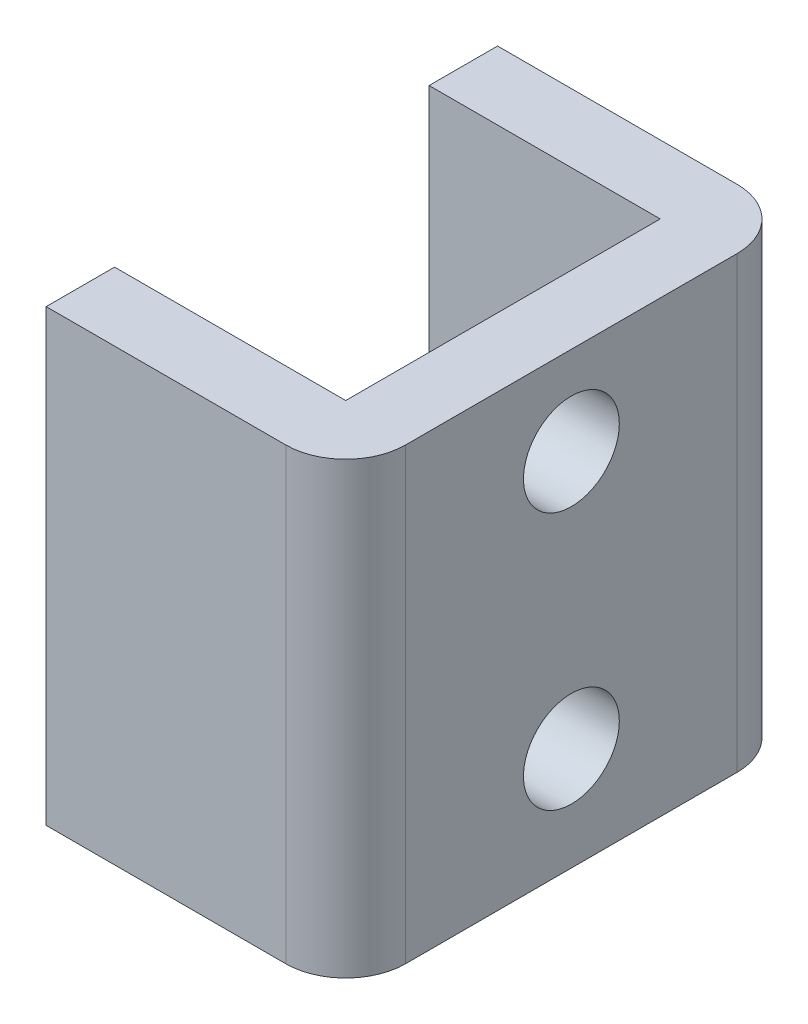
SolidWorks part; units mm, degrees
ref_plane "前视基准面" through (0, 0, 0) normal (0, 0, 1) x (1, 0, 0)
ref_plane "上视基准面" through (0, 0, 0) normal (0, 1, 0) x (1, 0, 0)
ref_plane "右视基准面" through (0, 0, 0) normal (1, 0, 0) x (0, 0, -1)
sketch "草图1" plane through (0, 0, 0) normal (0, 1, 0) x (1, 0, 0)
  line L0 (-35.9413, 35.7929) -> (-35.9413, 20.7229)
  line L1 (-35.9413, 20.7229) -> (-27.9413, 20.7229)
  line L2 (-35.9413, 35.7929) -> (-27.9413, 35.7929)
  line L3 (-25.9413, 33.7929) -> (-25.9413, 22.7229)
  arc A1 (-27.9413, 35.7929) -> (-25.9413, 33.7929) centre (-27.9413, 33.7929) cw
  arc A2 (-27.9413, 20.7229) -> (-25.9413, 22.7229) centre (-27.9413, 22.7229) ccw
  point P8 (-25.9413, 35.7929)
  point P11 (-25.9413, 20.7229)
  dimension "D1" = 10
  dimension "D3" = 2
  dimension "D4" = 2
  dimension "D2" = 15.07
sketch "草图5" plane through (0, 0, 0) normal (0, 1, 0) x (1, 0, 0)
extrude "凸台-拉伸4" add sketch "草图1" along normal blind 15
sketch "草图6" plane through (0, 15, 0) normal (0, 1, 0) x (1, 0, 0)
  line L0 (-33.6563, 33.5079) -> (-35.9413, 33.5079)
  line L1 (-35.9413, 35.7929) -> (-35.9413, 20.7229) construction
  line L2 (-35.9413, 33.5079) -> (-35.9413, 23.0079)
  line L3 (-35.9413, 23.0079) -> (-33.6563, 23.0079)
  line L4 (-33.6563, 33.5079) -> (-33.6563, 23.0079)
  line L8 (-28.2263, 33.5079) -> (-33.6563, 33.5079)
  line L9 (-33.6563, 33.5079) -> (-33.6563, 23.0079)
  line L10 (-33.6563, 23.0079) -> (-28.2263, 23.0079)
  line L11 (-28.2263, 23.0079) -> (-28.2263, 33.5079)
  line L12 (-28.2263, 33.5079) -> (-33.6563, 33.5079)
  line L13 (-33.6563, 33.5079) -> (-33.6563, 23.0079)
  line L14 (-33.6563, 23.0079) -> (-28.2263, 23.0079)
  line L15 (-28.2263, 23.0079) -> (-28.2263, 33.5079)
  dimension "D1" = 2.285
extrude "切除-拉伸2" cut sketch "草图6" against normal blind 15
sketch "草图7" plane through (0, 15, 0) normal (0, 1, 0) x (1, 0, 0)
  line L0 (-33.6563, 33.5079) -> (-35.9413, 33.5079)
  line L1 (-35.9413, 35.7929) -> (-35.9413, 20.7229) construction
  line L2 (-35.9413, 33.5079) -> (-35.9413, 23.0079)
  line L3 (-35.9413, 23.0079) -> (-33.6563, 23.0079)
  line L4 (-33.6563, 33.5079) -> (-33.6563, 23.0079) construction
  line L5 (-33.6563, 23.0079) -> (-33.6563, 33.5079)
extrude "切除-拉伸3" cut sketch "草图7" against normal blind 15
sketch "草图8" plane through (-25.9413, 0, 0) normal (1, 0, 0) x (0, 0, -1)
  line L5 (22.7229, 15) -> (22.7229, 0) construction
  circle A0 centre (28.2579, 12.0499) radius 1.6
  circle A1 centre (28.2579, 3.4499) radius 1.6
  point P12 (25.5641, 12.0499)
  dimension "D5" = 3.2
  dimension "D6" = 3.2
  dimension "D7" = 8.6
  dimension "D8" = 5.535
extrude "切除-拉伸4" cut sketch "草图8" against normal blind 10
